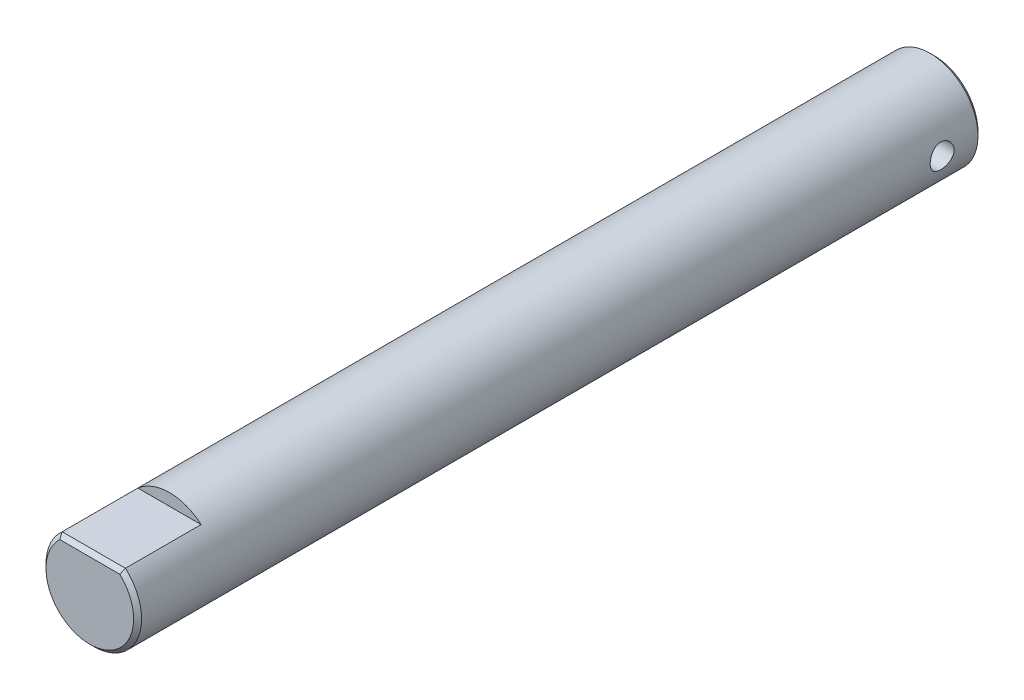
SolidWorks part; units mm, degrees
ref_plane "Front Plane" through (0, 0, 0) normal (0, 0, 1) x (1, 0, 0)
ref_plane "Top Plane" through (0, 0, 0) normal (0, 1, 0) x (1, 0, 0)
ref_plane "Right Plane" through (0, 0, 0) normal (1, 0, 0) x (0, 0, -1)
sketch "Sketch1" plane through (0, 0, 0) normal (0, 0, 1) x (1, 0, 0)
  circle A0 centre (0, 0) radius 6
  dimension "D1" = 12
extrude "Boss-Extrude1" add sketch "Sketch1" against normal blind 106
sketch "Sketch2" plane through (0, 0, 0) normal (1, 0, 0) x (0, 0, -1)
  line L0 (106, -6) -> (106, 6) construction
  circle A0 centre (101, 0) radius 1.5
  dimension "D1" = 3
  dimension "D2" = 5
extrude "Cut-Extrude1" cut sketch "Sketch2" along normal through all both and the other way through all
sketch "Sketch3" plane through (0, 0, 0) normal (0, 0, 1) x (1, 0, 0)
  line L0 (-3.9686, 4.5) -> (3.9686, 4.5)
  circle A0 centre (0, 0) radius 6 construction
  arc A1 (3.9686, 4.5) -> (-3.9686, 4.5) centre (0, 0) ccw
  dimension "D1" = 4.5
extrude "Cut-Extrude2" cut sketch "Sketch3" against normal blind 10
chamfer "Chamfer1" distance 0.5 angle 45 3 edges at (0, -6, 0) (0, 4.5, 0) (6, 0, -106)
